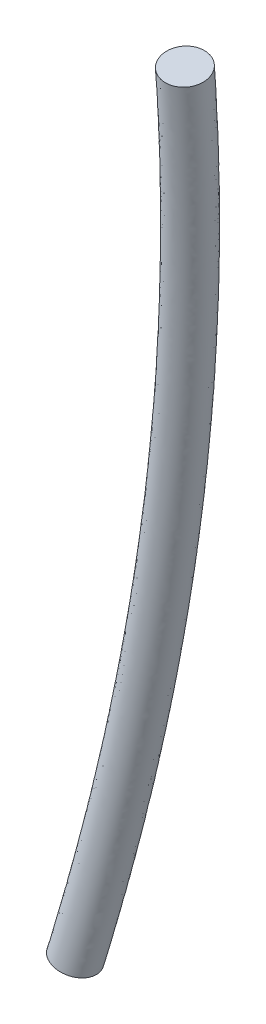
SolidWorks part; units mm, degrees
material "Custom Plastic"
ref_plane "X-Y Datum" through (0, 0, 0) normal (0, 0, 1) x (1, 0, 0)
ref_plane "X-Z Datum" through (0, 0, 0) normal (0, 1, 0) x (1, 0, 0)
ref_plane "Y-Z Datum" through (0, 0, 0) normal (1, 0, 0) x (0, 0, -1)
sketch3d "3DSketch1"
  circle A0 centre (-19, -40.3793, 237.3572) radius 2.286 construction
  circle A1 centre (-38.9257, -165.2645, 232.3735) radius 4.5 construction
  spline S0 degree 2 poles (-19, -40.3793, 237.3572) (-24.1775, -106.7506, 227.7028) (-40.2627, -170.658, 232.775) knots 0 0 0 1 1 1
  point P2 (-50.662, -167.5939, 226.7374)
  point P4 (-44.0309, -172.4978, 234.5909)
  point P5 (0, 0, 0)
  point P8 (-19, -42.6653, 237.3572)
  point P11 (-38.1443, -160.8329, 232.3735)
  point P12 (-40.5865, -176.1575, 234.5909)
  point P13 (0, 0, 0)
  point P14 (-40.5865, -176.6007, 232.9291)
  point P15 (-39.0668, -170.8253, 234.9107)
  point P16 (-39.0668, -170.5583, 232.775)
  point P17 (-40.2627, -170.658, 232.775)
sweep "Sweep1" add path "3DSketch1" circular profile diameter 6.35 parameters "D3"=6.35
